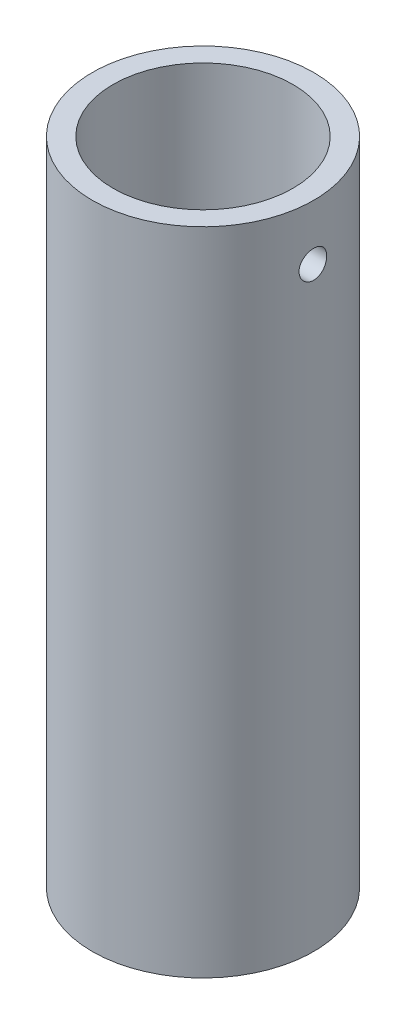
SolidWorks part; units mm, degrees
material "AISI 304"
ref_plane "Front Plane" through (0, 0, 0) normal (0, 0, 1) x (1, 0, 0)
ref_plane "Top Plane" through (0, 0, 0) normal (0, 1, 0) x (1, 0, 0)
ref_plane "Right Plane" through (0, 0, 0) normal (1, 0, 0) x (0, 0, -1)
sketch "Sketch3" plane through (0, 0, 0) normal (0, 1, 0) x (1, 0, 0)
  circle A0 centre (0, 0) radius 8
  dimension "D1" = 16
extrude "Extrude-Thin1" add sketch "Sketch3" along normal mid plane 47 thin contours A0 thin type one direction reverse wall 1.5
hole_wizard "Ø2.0mm Dowel Hole1" positions "3DSketch1" profile "Sketch4" hole size "Ø2.0" standard "ISO"
sketch3d "3DSketch1"
  point P0 (8, 19.5, 0)
  dimension "D1" = 43
sketch "Sketch4" plane through (8, 19.5, 0) normal (0, 1, 0) x (0, 0, -1)
  line L0 (0, 0) -> (0, 1.5)
  line L1 (0, 1.5) -> (1, 1.5)
  line L2 (1, 1.5) -> (1, 0)
  line L5 (1, 0) -> (0, 0)
  line L11 (0, -6.35) -> (0, 107.95) construction
  dimension "Thru Hole Dia." = 2
  dimension "Thru Hole Depth" = 1.5
